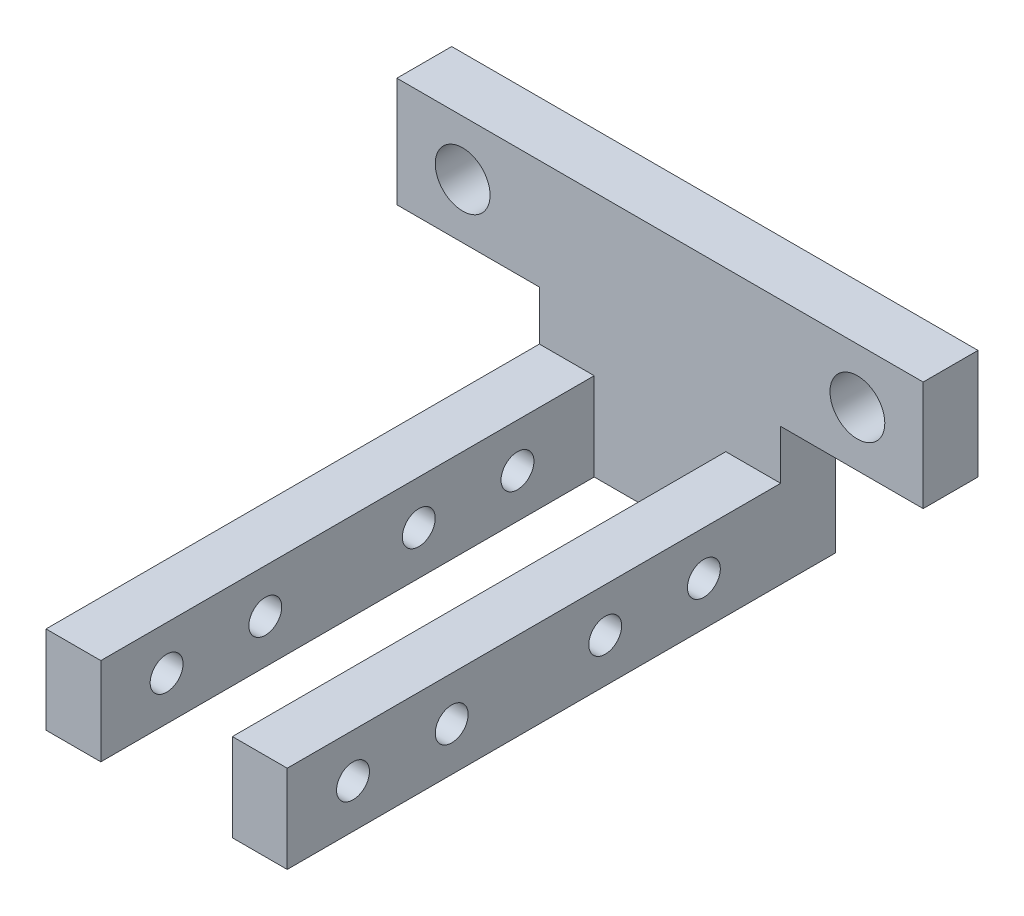
SolidWorks part; units mm, degrees
ref_plane "前视基准面" through (0, 0, 0) normal (0, 0, 1) x (1, 0, 0)
ref_plane "上视基准面" through (0, 0, 0) normal (0, 1, 0) x (1, 0, 0)
ref_plane "右视基准面" through (0, 0, 0) normal (1, 0, 0) x (0, 0, -1)
sketch "草图1" plane through (0, 0, 0) normal (0, 0, 1) x (1, 0, 0)
  line L0 (-18.0161, 6.3887) -> (-12.0161, 6.3887) construction
  line L1 (-18.0161, 11.3887) -> (29.9839, 11.3887)
  line L2 (-18.0161, 11.3887) -> (-18.0161, 1.3887)
  line L3 (-18.0161, 1.3887) -> (29.9839, 1.3887)
  line L4 (29.9839, 11.3887) -> (29.9839, 1.3887)
  line L5 (29.9839, 6.3887) -> (23.9839, 6.3887) construction
  line L6 (5.9839, 11.3887) -> (5.9839, 1.3887) construction
  line L7 (-5.0161, 6.3887) -> (16.9839, 6.3887)
  line L9 (-5.0161, 6.3887) -> (16.9839, 6.3887)
  line L10 (-5.0161, 6.3887) -> (-5.0161, -11.1113)
  line L11 (-5.0161, -11.1113) -> (16.9839, -11.1113)
  line L12 (16.9839, 6.3887) -> (16.9839, -11.1113)
  circle A0 centre (-12.0161, 6.3887) radius 2.5
  circle A1 centre (23.9839, 6.3887) radius 2.5
  point P15 (5.9839, 6.3887)
  dimension "D5" = 22
  dimension "D1" = 48
  dimension "D2" = 10
  dimension "D3" = 6
  dimension "D4" = 6
  dimension "D6" = 17.5
extrude "凸台-拉伸2" add sketch "草图1" along normal blind 5 contours L7 L12 L3 L4 L1 L2 L10 A1 A0 | L12 L3 L10 L11 | L12 L7 L10 L3
sketch "草图2" plane through (0, 0, 5) normal (0, 0, 1) x (1, 0, 0)
  line L1 (-5.0161, -11.1113) -> (-0.0161, -11.1113)
  line L2 (-5.0161, -11.1113) -> (-5.0161, -3.1113)
  line L3 (-5.0161, -3.1113) -> (-0.0161, -3.1113)
  line L4 (-0.0161, -11.1113) -> (-0.0161, -3.1113)
  line L5 (16.9839, -11.1113) -> (11.9839, -11.1113)
  line L6 (16.9839, -11.1113) -> (16.9839, -3.1113)
  line L7 (16.9839, -3.1113) -> (11.9839, -3.1113)
  line L8 (11.9839, -11.1113) -> (11.9839, -3.1113)
  dimension "D1" = 5
  dimension "D2" = 8
  dimension "D3" = 5
  dimension "D4" = 8
extrude "凸台-拉伸3" add sketch "草图2" along normal blind 45
sketch "草图3" plane through (-5.0161, 0, 0) normal (-1, 0, 0) x (0, 0, 1)
  line L0 (5, -3.1113) -> (5, -11.1113) construction
  line L1 (50, -3.1113) -> (5, -3.1113) construction
  line L2 (50, -11.1113) -> (0, -11.1113) construction
  line L3 (5, -7.1113) -> (21, -7.1113) construction
  line L4 (21, -7.1113) -> (35, -7.1113) construction
  circle A0 centre (21, -7.1113) radius 1.5
  circle A1 centre (35, -7.1113) radius 1.5
  point P9 (0, 0)
  point P12 (0, 0)
  point P13 (0, 0)
  point P14 (0, 0)
  dimension "D2" = 14
  dimension "D1" = 16
extrude "切除-拉伸1" cut sketch "草图3" against normal blind 45
sketch "草图5" plane through (-5.0161, 0, 0) normal (-1, 0, 0) x (0, 0, 1)
  line L0 (22.5, -7.1113) -> (33.5, -7.1113) construction
  line L1 (12, -7.1113) -> (44, -7.1113)
  circle A0 centre (21, -7.1113) radius 1.5 construction
  circle A1 centre (35, -7.1113) radius 1.5 construction
  circle A2 centre (44, -7.1113) radius 1.5
  circle A3 centre (12, -7.1113) radius 1.5
  point P10 (28, -7.1113)
  dimension "D1" = 32
extrude "切除-拉伸2" cut sketch "草图5" against normal blind 45 contours A3 | A2
